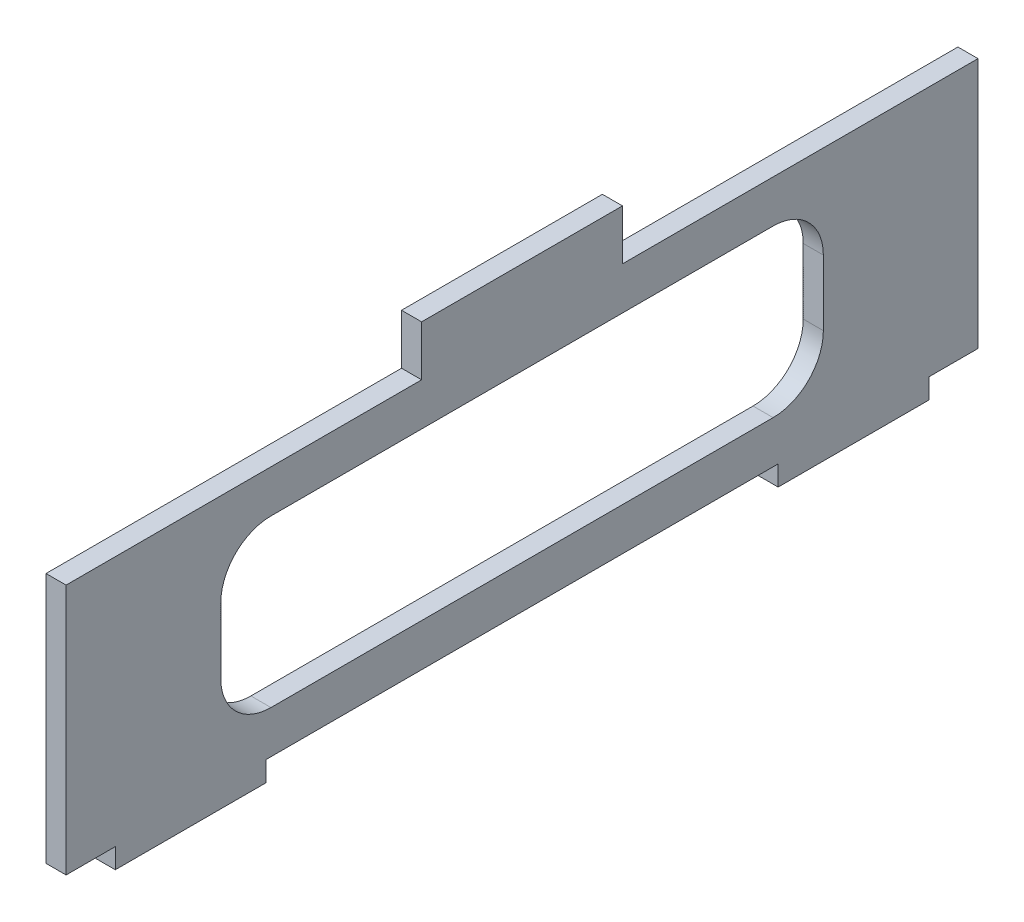
SolidWorks part; units mm, degrees
material "Aleación 6061"
ref_plane "Alzado" through (0, 0, 0) normal (0, 0, 1) x (1, 0, 0)
ref_plane "Planta" through (0, 0, 0) normal (0, 1, 0) x (1, 0, 0)
ref_plane "Vista lateral" through (0, 0, 0) normal (1, 0, 0) x (0, 0, -1)
sketch "Croquis1" plane through (0, 0, 0) normal (1, 0, 0) x (0, 0, -1)
  line L0 (-81, -25) -> (-81, -29)
  line L1 (-90.8, -25) -> (-81, -25)
  line L2 (-90.8, -25) -> (-90.8, 25)
  line L3 (-90.8, 25) -> (-20, 25)
  line L4 (90.8, -25) -> (90.8, 25)
  line L5 (-90.8, -25) -> (90.8, 25) construction
  line L6 (-90.8, 25) -> (90.8, -25) construction
  line L7 (-81, -29) -> (-51, -29)
  line L8 (-51, -29) -> (-51, -25)
  line L9 (-20, 25) -> (-20, 35)
  line L10 (-20, 35) -> (20, 35)
  line L11 (20, 35) -> (20, 25)
  line L12 (51, -25) -> (51, -29)
  line L13 (51, -29) -> (81, -29)
  line L14 (81, -29) -> (81, -25)
  line L15 (-51, -25) -> (51, -25)
  line L16 (20, 25) -> (90.8, 25)
  line L17 (81, -25) -> (90.8, -25)
  line L19 (-50, 16.5198) -> (50, 16.5198)
  line L20 (-60, 6.5198) -> (-60, -6.5198)
  line L21 (-50, -16.5198) -> (50, -16.5198)
  line L22 (60, 6.5198) -> (60, -6.5198)
  line L23 (-60, 16.5198) -> (60, -16.5198) construction
  line L24 (-60, -16.5198) -> (60, 16.5198) construction
  arc A0 (50, 16.5198) -> (60, 6.5198) centre (50, 6.5198) cw
  arc A1 (60, -6.5198) -> (50, -16.5198) centre (50, -6.5198) cw
  arc A2 (-60, -6.5198) -> (-50, -16.5198) centre (-50, -6.5198) ccw
  arc A3 (-50, 16.5198) -> (-60, 6.5198) centre (-50, 6.5198) ccw
  point P0 (0, 0)
  point P17 (0, 35)
  point P18 (0, 0)
  dimension "D10" = 10
  dimension "D1" = 50
  dimension "D2" = 181.6
  dimension "D3" = 9.8
  dimension "D4" = 9.8
  dimension "D5" = 4
  dimension "D6" = 30
  dimension "D7" = 40
  dimension "D8" = 10
  dimension "D9" = 120
extrude "Saliente-Extruir1" add sketch "Croquis1" along normal blind 4
